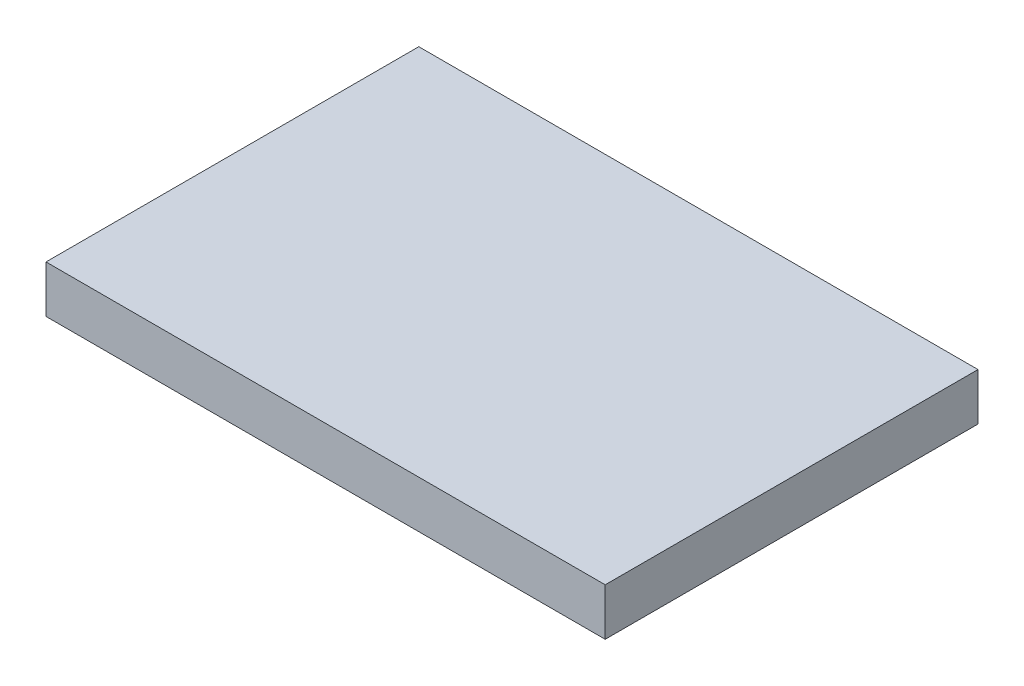
SolidWorks part; units mm, degrees
ref_plane "Front Plane" through (0, 0, 0) normal (0, 0, 1) x (1, 0, 0)
ref_plane "Top Plane" through (0, 0, 0) normal (0, 1, 0) x (1, 0, 0)
ref_plane "Right Plane" through (0, 0, 0) normal (1, 0, 0) x (0, 0, -1)
sketch "Sketch1" plane through (0, 0, 0) normal (0, 1, 0) x (1, 0, 0)
  line L1 (225, -150) -> (-225, -150)
  line L2 (225, -150) -> (225, 150)
  line L3 (225, 150) -> (-225, 150)
  line L4 (-225, -150) -> (-225, 150)
  line L5 (225, -150) -> (-225, 150) construction
  line L6 (225, 150) -> (-225, -150) construction
  point P0 (0, 0)
  dimension "D1" = 450
  dimension "D2" = 300
extrude "Boss-Extrude1" add sketch "Sketch1" along normal blind 38
shell "Shell1" thickness 4
